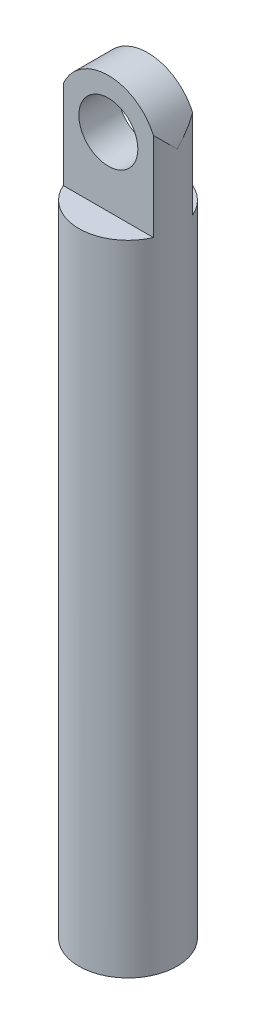
SolidWorks part; units mm, degrees
ref_plane "前视基准面" through (0, 0, 0) normal (0, 0, 1) x (1, 0, 0)
ref_plane "上视基准面" through (0, 0, 0) normal (0, 1, 0) x (1, 0, 0)
ref_plane "右视基准面" through (0, 0, 0) normal (1, 0, 0) x (0, 0, -1)
sketch "草图1" plane through (0, 0, 0) normal (0, 1, 0) x (1, 0, 0)
  circle A0 centre (0, 0) radius 2.5
  dimension "D1" = 5
extrude "凸台-拉伸1" add sketch "草图1" along normal blind 38.5
sketch "草图2" plane through (0, 0, 0) normal (0, 0, 1) x (1, 0, 0)
  line L0 (0, 39.9923) -> (0, -1.0757) construction
  line L1 (2.5, 38.5) -> (-2.5, 38.5) construction
  line L2 (-2.5, 38.5) -> (-2.5, 0) construction
  line L3 (2.5, 0) -> (2.5, 38.5) construction
  line L7 (2.5, 36) -> (2.5, 38.5)
  line L8 (2.5, 38.5) -> (-2.5, 38.5)
  line L9 (-2.5, 38.5) -> (-2.5, 36)
  circle A0 centre (0, 36) radius 1.5
  arc A1 (-2.5, 36) -> (2.5, 36) centre (0, 36) cw
  dimension "D2" = 3
  dimension "D3" = 2.5
  dimension "D1" = 2.5
extrude "切除-拉伸1" cut sketch "草图2" against normal through all both and the other way through all
sketch "草图3" plane through (0, 0, 0) normal (1, 0, 0) x (0, 0, -1)
  line L0 (0, 38.5) -> (0, 0) construction
  line L1 (-2.5, 38.5) -> (4.2247, 38.5) construction
  line L6 (0, 36) -> (2.5, 38.5) construction
  line L7 (-2.5, 38.5) -> (-1, 38.5)
  line L8 (-2.5, 38.5) -> (-2.5, 32.5)
  line L9 (-2.5, 32.5) -> (-1, 32.5)
  line L10 (-1, 38.5) -> (-1, 32.5)
  line L11 (2.5, 38.5) -> (1, 38.5)
  line L12 (2.5, 38.5) -> (2.5, 32.5)
  line L13 (2.5, 32.5) -> (1, 32.5)
  line L14 (1, 38.5) -> (1, 32.5)
  dimension "D1" = 1.5
  dimension "D2" = 1.5
  dimension "D3" = 6
  dimension "D4" = 6
extrude "切除-拉伸2" cut sketch "草图3" against normal through all both and the other way through all
